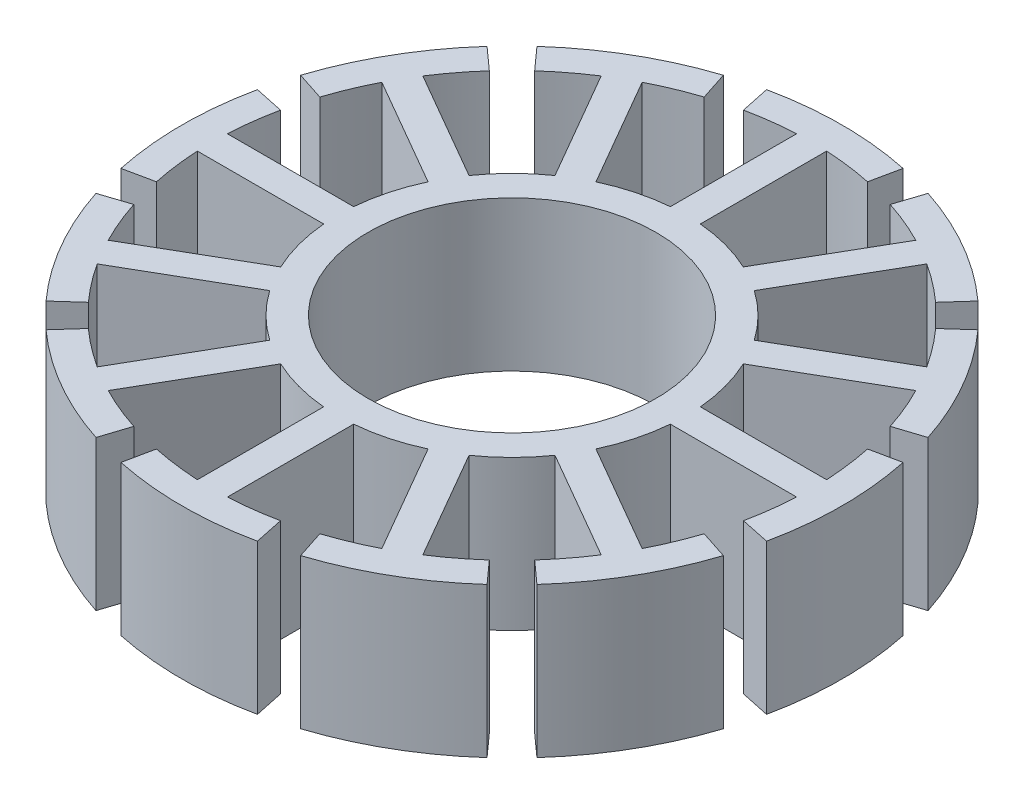
SolidWorks part; units mm, degrees
ref_plane "Front Plane" through (0, 0, 0) normal (0, 0, 1) x (1, 0, 0)
ref_plane "Top Plane" through (0, 0, 0) normal (0, 1, 0) x (1, 0, 0)
ref_plane "Right Plane" through (0, 0, 0) normal (1, 0, 0) x (0, 0, -1)
sketch "Sketch1" plane through (0, 0, 0) normal (0, 1, 0) x (1, 0, 0)
  line L0 (0, 11) -> (0, -11) construction
  line L1 (-0.5, 9.9875) -> (-0.5, 5.7784)
  line L2 (0.5, 9.9875) -> (0.5, 5.7784)
  line L3 (-2.0682, 9.7838) -> (-2.275, 10.7622)
  line L4 (2.0682, 9.7838) -> (2.275, 10.7622)
  line L5 (3.1008, 9.5071) -> (3.4109, 10.4578)
  line L6 (4.5607, 8.8994) -> (2.4562, 5.2542)
  line L7 (5.4268, 8.3994) -> (3.3222, 4.7542)
  line L8 (6.683, 7.4389) -> (7.3513, 8.1828)
  line L9 (7.4389, 6.683) -> (8.1828, 7.3513)
  line L10 (8.3994, 5.4268) -> (4.7542, 3.3222)
  line L11 (8.8994, 4.5607) -> (5.2542, 2.4562)
  line L12 (9.5071, 3.1008) -> (10.4578, 3.4109)
  line L13 (9.7838, 2.0682) -> (10.7622, 2.275)
  line L14 (9.9875, 0.5) -> (5.7784, 0.5)
  line L15 (9.9875, -0.5) -> (5.7784, -0.5)
  line L16 (9.7838, -2.0682) -> (10.7622, -2.275)
  line L17 (9.5071, -3.1008) -> (10.4578, -3.4109)
  line L18 (8.8994, -4.5607) -> (5.2542, -2.4562)
  line L19 (8.3994, -5.4268) -> (4.7542, -3.3222)
  line L20 (7.4389, -6.683) -> (8.1828, -7.3513)
  line L21 (6.683, -7.4389) -> (7.3513, -8.1828)
  line L22 (5.4268, -8.3994) -> (3.3222, -4.7542)
  line L23 (4.5607, -8.8994) -> (2.4562, -5.2542)
  line L24 (3.1008, -9.5071) -> (3.4109, -10.4578)
  line L25 (2.0682, -9.7838) -> (2.275, -10.7622)
  line L26 (0.5, -9.9875) -> (0.5, -5.7784)
  line L27 (-0.5, -9.9875) -> (-0.5, -5.7784)
  line L28 (-2.0682, -9.7838) -> (-2.275, -10.7622)
  line L29 (-3.1008, -9.5071) -> (-3.4109, -10.4578)
  line L30 (-4.5607, -8.8994) -> (-2.4562, -5.2542)
  line L31 (-5.4268, -8.3994) -> (-3.3222, -4.7542)
  line L32 (-6.683, -7.4389) -> (-7.3513, -8.1828)
  line L33 (-7.4389, -6.683) -> (-8.1828, -7.3513)
  line L34 (-8.3994, -5.4268) -> (-4.7542, -3.3222)
  line L35 (-8.8994, -4.5607) -> (-5.2542, -2.4562)
  line L36 (-9.5071, -3.1008) -> (-10.4578, -3.4109)
  line L37 (-9.7838, -2.0682) -> (-10.7622, -2.275)
  line L38 (-9.9875, -0.5) -> (-5.7784, -0.5)
  line L39 (-9.9875, 0.5) -> (-5.7784, 0.5)
  line L40 (-9.7838, 2.0682) -> (-10.7622, 2.275)
  line L41 (-9.5071, 3.1008) -> (-10.4578, 3.4109)
  line L42 (-8.8994, 4.5607) -> (-5.2542, 2.4562)
  line L43 (-8.3994, 5.4268) -> (-4.7542, 3.3222)
  line L44 (-7.4389, 6.683) -> (-8.1828, 7.3513)
  line L45 (-6.683, 7.4389) -> (-7.3513, 8.1828)
  line L46 (-5.4268, 8.3994) -> (-3.3222, 4.7542)
  line L47 (-4.5607, 8.8994) -> (-2.4562, 5.2542)
  line L48 (-3.1008, 9.5071) -> (-3.4109, 10.4578)
  circle A0 centre (0, 0) radius 4.8
  circle A1 centre (0, 0) radius 5.8
  circle A2 centre (0, 0) radius 11
  circle A3 centre (0, 0) radius 10
  point P106 (0, 0)
  dimension "D1" = 9.6
  dimension "D2" = 1
  dimension "D3" = 22
  dimension "D6" = 1
  dimension "D7" = 4.55
  dimension "D4" = 1
  dimension "D5" = 12
extrude "Boss-Extrude1" add sketch "Sketch1" along normal blind 5 contours A1 L0 A0 | L0 A1 A0 | L0 A3 L1 A1 | A3 L0 A1 L2 | A2 L0 A3 L4 | L0 A2 L3 A3 | L7 A3 L6 A1 | A3 L8 A2 L5 | L11 A3 L10 A1 | A3 L12 A2 L9 | L15 A3 L14 A1 | A3 L16 A2 L13 | L19 A3 L18 A1 | A3 L20 A2 L17 | L23 A3 L22 A1 | A3 L24 A2 L21 | L0 A1 L27 A3 | A1 L0 A3 L26 | A3 L0 A2 L25 | L0 A3 L28 A2 | L31 A3 L30 A1 | A3 L32 A2 L29 | L35 A3 L34 A1 | A3 L36 A2 L33 | L39 A3 L38 A1 | A3 L40 A2 L37 | L43 A3 L42 A1 | A3 L44 A2 L41 | L47 A3 L46 A1 | A3 L48 A2 L45
